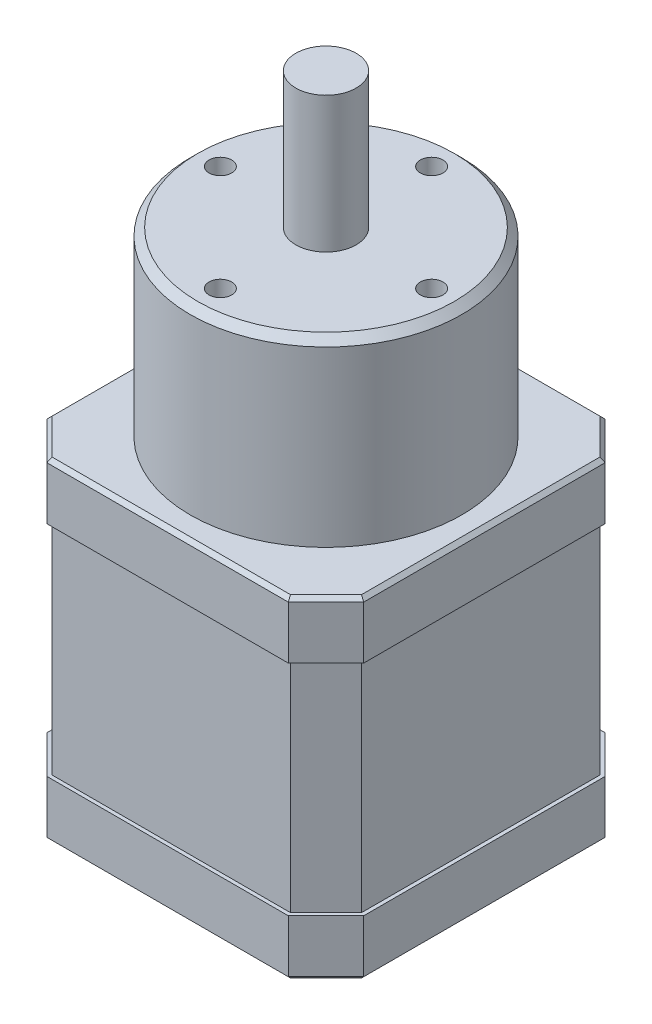
SolidWorks part; units mm, degrees
ref_plane "Front Plane" through (0, 0, 0) normal (0, 0, 1) x (1, 0, 0)
ref_plane "Top Plane" through (0, 0, 0) normal (0, 1, 0) x (1, 0, 0)
ref_plane "Right Plane" through (0, 0, 0) normal (1, 0, 0) x (0, 0, -1)
sketch "Sketch1" plane through (0, 0, 0) normal (0, 1, 0) x (1, 0, 0)
  line L1 (-21, 21) -> (21, 21)
  line L2 (-21, 21) -> (-21, -21)
  line L3 (-21, -21) -> (21, -21)
  line L4 (21, 21) -> (21, -21)
  line L5 (-21, 21) -> (21, -21) construction
  line L6 (-21, -21) -> (21, 21) construction
  point P0 (0, 0)
  dimension "D1" = 42
extrude "Boss-Extrude1" add sketch "Sketch1" along normal blind 44
sketch "Sketch2" plane through (0, 44, 0) normal (0, 1, 0) x (1, 0, 0)
  circle A0 centre (0, 0) radius 18
  dimension "D1" = 36
extrude "Boss-Extrude2" add sketch "Sketch2" along normal blind 24 contours A0
sketch "Sketch3" plane through (0, 68, 0) normal (0, 1, 0) x (1, 0, 0)
  circle A0 centre (0, 0) radius 4
  dimension "D1" = 8
extrude "Boss-Extrude3" add sketch "Sketch3" along normal blind 18
chamfer "Chamfer1" distance 5 angle 45 4 edges at (-21, 22, -21) (21, 22, -21) (21, 22, 21) (-21, 22, 21)
sketch "Sketch4" plane through (0, 68, 0) normal (0, 1, 0) x (1, 0, 0)
  circle A0 centre (0, 14) radius 1.5
  circle A3 centre (0, 0) radius 18 construction
  dimension "D1" = 3
  dimension "D2" = 14
extrude "Cut-Extrude1" cut sketch "Sketch4" against normal blind 10 contours A0
pattern_circular "CirPattern1" count 4 over 360 about axis through (0, 0, 0) along (0, 1, 0) of "Cut-Extrude1"
chamfer "Chamfer2" distance 1 angle 45 1 edges at (0, 68, 18)
sketch "Sketch5" plane through (0, 0, 0) normal (0, -1, 0) x (1, 0, 0)
  line L16 (-20.5, 15.7929) -> (-20.5, -15.7929)
  line L17 (-20.5, -15.7929) -> (-15.7929, -20.5)
  line L18 (-15.7929, -20.5) -> (15.7929, -20.5)
  line L19 (15.7929, -20.5) -> (20.5, -15.7929)
  line L20 (20.5, -15.7929) -> (20.5, 15.7929)
  line L21 (20.5, 15.7929) -> (15.7929, 20.5)
  line L22 (15.7929, 20.5) -> (-15.7929, 20.5)
  line L23 (-15.7929, 20.5) -> (-20.5, 15.7929)
  line L24 (-20.5, 15.7929) -> (-20.5, -15.7929)
  line L25 (-20.5, -15.7929) -> (-15.7929, -20.5)
  line L26 (-15.7929, -20.5) -> (15.7929, -20.5)
  line L27 (15.7929, -20.5) -> (20.5, -15.7929)
  line L28 (20.5, -15.7929) -> (20.5, 15.7929)
  line L29 (20.5, 15.7929) -> (15.7929, 20.5)
  line L30 (15.7929, 20.5) -> (-15.7929, 20.5)
  line L31 (-15.7929, 20.5) -> (-20.5, 15.7929)
  line L40 (-21, 16) -> (-21, -16)
  line L41 (-21, -16) -> (-16, -21)
  line L42 (-16, -21) -> (16, -21)
  line L43 (16, -21) -> (21, -16)
  line L44 (21, -16) -> (21, 16)
  line L45 (21, 16) -> (16, 21)
  line L46 (16, 21) -> (-16, 21)
  line L47 (-16, 21) -> (-21, 16)
  line L48 (-21, 16) -> (-21, -16)
  line L49 (-21, -16) -> (-16, -21)
  line L50 (-16, -21) -> (16, -21)
  line L51 (16, -21) -> (21, -16)
  line L52 (21, -16) -> (21, 16)
  line L53 (21, 16) -> (16, 21)
  line L54 (16, 21) -> (-16, 21)
  line L55 (-16, 21) -> (-21, 16)
  dimension "D1" = 0.5
  dimension "D2" = 0
extrude "Cut-Extrude2" cut sketch "Sketch5" against normal offset from surface (29 mm away) 7.5 from offset 7.5 up to face at (0, 44, 18) offset against normal yes
chamfer "Chamfer4" distance 0.5 angle 45 16 edges at (18.5, 44, -18.5) (21, 44, 0) (18.5, 44, 18.5) (0, 44, 21) (-18.5, 44, 18.5) (-21, 44, 0) (-18.5, 44, -18.5) (0, 44, -21) (-18.5, 0, 18.5) (0, 0, 21) (18.5, 0, 18.5) (21, 0, 0) (18.5, 0, -18.5) (0, 0, -21) (-18.5, 0, -18.5) (-21, 0, 0)
